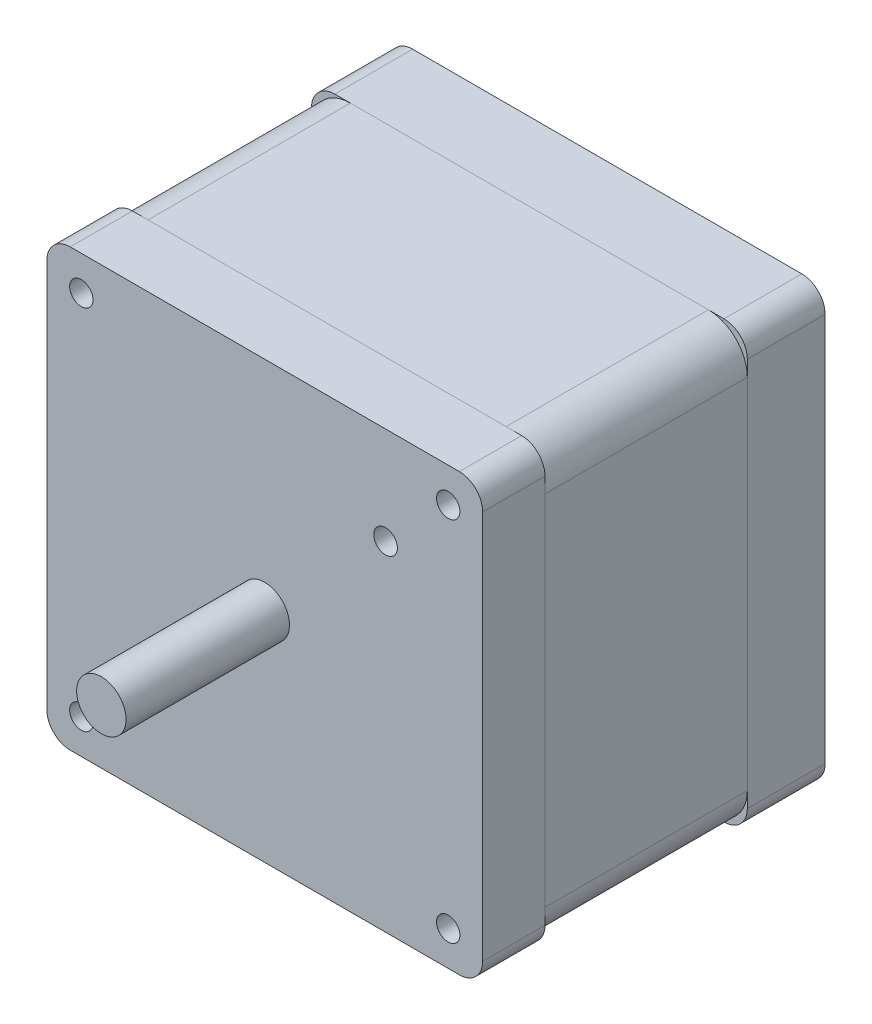
SolidWorks part; units mm, degrees
ref_plane "前视基准面" through (0, 0, 0) normal (0, 0, 1) x (1, 0, 0)
ref_plane "上视基准面" through (0, 0, 0) normal (0, 1, 0) x (1, 0, 0)
ref_plane "右视基准面" through (0, 0, 0) normal (1, 0, 0) x (0, 0, -1)
sketch "草图1" plane through (0, 0, 0) normal (0, 0, 1) x (1, 0, 0)
  line L0 (0, 28) -> (0, -28) construction
  line L1 (-25, 28) -> (25, 28)
  line L2 (-28, 25) -> (-28, -25)
  line L3 (-25, -28) -> (25, -28)
  line L4 (28, 25) -> (28, -25)
  line L5 (-28, 28) -> (28, -28) construction
  line L6 (-28, -28) -> (28, 28) construction
  line L7 (-23.57, 23.57) -> (23.57, 23.57) construction
  line L8 (-23.57, 23.57) -> (-23.57, -23.57) construction
  line L9 (-23.57, -23.57) -> (23.57, -23.57) construction
  line L10 (23.57, 23.57) -> (23.57, -23.57) construction
  line L11 (-23.57, 23.57) -> (23.57, -23.57) construction
  line L12 (-23.57, -23.57) -> (23.57, 23.57) construction
  line L13 (-28, 0) -> (28, 0) construction
  circle A0 centre (-23.57, 23.57) radius 1.5
  circle A1 centre (23.57, 23.57) radius 1.5
  circle A2 centre (23.57, -23.57) radius 1.5
  circle A3 centre (-23.57, -23.57) radius 1.5
  arc A4 (-25, -28) -> (-28, -25) centre (-25, -25) cw
  arc A5 (25, -28) -> (28, -25) centre (25, -25) ccw
  arc A6 (28, 25) -> (25, 28) centre (25, 25) ccw
  arc A7 (-28, 25) -> (-25, 28) centre (-25, 25) cw
  point P0 (0, 0)
  point P6 (0, 0)
  dimension "D4" = 3
  dimension "D5" = 3
  dimension "D1" = 56
  dimension "D2" = 56
  dimension "D3" = 47.14
extrude "凸台-拉伸1" add sketch "草图1" along normal blind 8
sketch "草图4" plane through (0, 0, 8) normal (0, 0, 1) x (1, 0, 0)
  circle A0 centre (0, 0) radius 3.175
  dimension "D1" = 6.35
extrude "凸台-拉伸2" add sketch "草图4" along normal blind 21
sketch "草图9" plane through (0, 0, 0) normal (0, 0, -1) x (-1, 0, 0)
  line L1 (-28, 28) -> (28, 28)
  line L2 (-28, 28) -> (-28, -28)
  line L3 (-28, -28) -> (28, -28)
  line L4 (28, 28) -> (28, -28)
  line L5 (-28, 28) -> (28, -28) construction
  line L6 (-28, -28) -> (28, 28) construction
  point P0 (0, 0)
  dimension "D1" = 56
  dimension "D2" = 56
extrude "凸台-拉伸7" add sketch "草图9" along normal blind 26 separate body
sketch "草图10" plane through (0, 0, -26) normal (0, 0, -1) x (-1, 0, 0)
  line L1 (-28, 28) -> (28, 28)
  line L2 (-28, 28) -> (-28, -28)
  line L3 (-28, -28) -> (28, -28)
  line L4 (28, 28) -> (28, -28)
extrude "凸台-拉伸8" add sketch "草图10" along normal blind 10 separate body
fillet "圆角1" radius 3 4 edges at (28, -28, -31) (-28, -28, -31) (-28, 28, -31) (28, 28, -31)
fillet "圆角2" radius 5 4 edges at (-28, -28, -13) (-28, 28, -13) (28, 28, -13) (28, -28, -13)
sketch "草图12" plane through (0, 0, 8) normal (0, 0, 1) x (1, 0, 0)
  circle A0 centre (-23.57, 23.57) radius 1.5
  circle A1 centre (15.5185, 15.5) radius 1.5185
  circle A2 centre (-23.57, -23.57) radius 1.5
  circle A3 centre (23.57, -23.57) radius 1.5
extrude "切除-拉伸1" cut sketch "草图12" against normal through all
